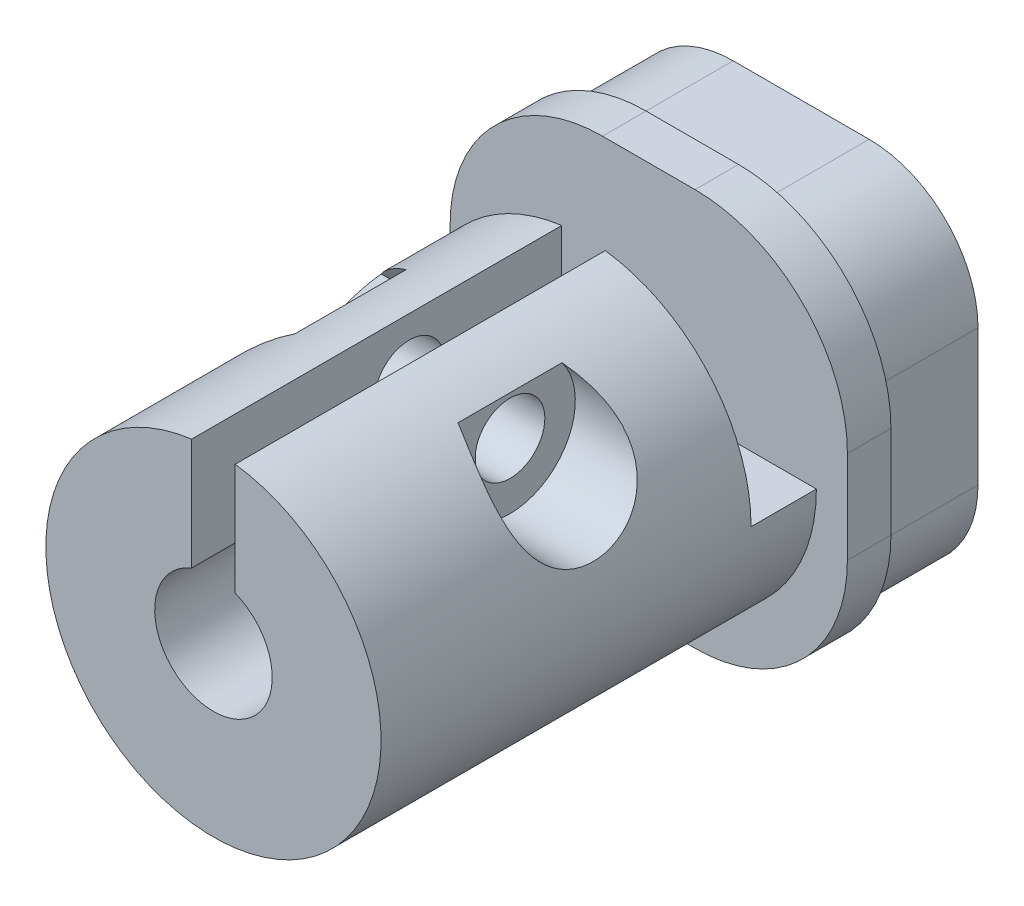
SolidWorks part; units mm, degrees
ref_plane "Płaszczyzna przednia" through (0, 0, 0) normal (0, 0, 1) x (1, 0, 0)
ref_plane "Płaszczyzna górna" through (0, 0, 0) normal (0, 1, 0) x (1, 0, 0)
ref_plane "Płaszczyzna prawa" through (0, 0, 0) normal (1, 0, 0) x (0, 0, -1)
sketch "Sketch1" plane through (0, 0, 0) normal (0, 0, 1) x (1, 0, 0)
  line L0 (6.125, 6.125) -> (-6.125, 6.125)
  line L1 (8.125, -8.125) -> (-8.125, -8.125)
  line L2 (8.125, -8.125) -> (8.125, 8.125)
  line L3 (8.125, 8.125) -> (-8.125, 8.125)
  line L4 (-8.125, -8.125) -> (-8.125, 8.125)
  line L5 (8.125, -8.125) -> (-8.125, 8.125) construction
  line L6 (8.125, 8.125) -> (-8.125, -8.125) construction
  line L7 (-6.125, -6.125) -> (-6.125, 6.125)
  line L8 (6.125, -6.125) -> (-6.125, -6.125)
  line L9 (6.125, -6.125) -> (6.125, 6.125)
  point P0 (0, 0)
  dimension "D1" = 16.25
  dimension "D2" = 2
extrude "Boss-Extrude1" add sketch "Sketch1" along normal blind 5
fillet "Fillet1" radius 5 8 edges at (-8.125, -8.125, 2.5) (8.125, -8.125, 2.5) (-8.125, 8.125, 2.5) (8.125, 8.125, 2.5) (6.125, -6.125, 2.5) (-6.125, -6.125, 2.5) (6.125, 6.125, 2.5) (-6.125, 6.125, 2.5)
sketch "Sketch2" plane through (0, 0, 5) normal (0, 0, 1) x (1, 0, 0)
  line L0 (-8.125, 3.125) -> (-8.125, -3.125) construction
  line L1 (9.125, 9.125) -> (-9.125, 9.125)
  line L2 (9.125, 9.125) -> (9.125, -9.125)
  line L3 (9.125, -9.125) -> (-9.125, -9.125)
  line L4 (-9.125, 9.125) -> (-9.125, -9.125)
  line L5 (9.125, 9.125) -> (-9.125, -9.125) construction
  line L6 (9.125, -9.125) -> (-9.125, 9.125) construction
  point P0 (0, 0)
  dimension "D1" = 1
extrude "Boss-Extrude2" add sketch "Sketch2" along normal blind 2
fillet "Fillet2" radius 7 4 edges at (9.125, -9.125, 6) (-9.125, -9.125, 6) (-9.125, 9.125, 6) (9.125, 9.125, 6)
sketch "Sketch3" plane through (0, 0, 7) normal (0, 0, 1) x (1, 0, 0)
  line L0 (0, 2.5) -> (0, 7.5) construction
  line L1 (1, 2.5) -> (1, 7.6348)
  line L2 (-1, 2.5) -> (-1, 7.6348)
  line L3 (1, 2.5) -> (1, 2.508)
  line L4 (-1, 2.5) -> (-1, 2.508)
  line L5 (-1, 2.5) -> (-1, 7.5) construction
  line L6 (1, 2.5) -> (1, 7.5) construction
  arc A0 (-1, 2.508) -> (1, 2.508) centre (0, 0) ccw
  arc A1 (-1, 7.6348) -> (1, 7.6348) centre (0, 0) ccw
  circle A2 centre (0, 0) radius 7.7 construction
  circle A3 centre (0, 0) radius 2.7 construction
  dimension "D1" = 5.4
  dimension "D2" = 5
  dimension "D3" = 1
  dimension "D4" = 1
extrude "Boss-Extrude3" add sketch "Sketch3" along normal blind 20 contours L2 A1 L1 A0
sketch "Sketch5" plane through (0, 0, 0) normal (1, 0, 0) x (0, 0, -1)
  line L0 (-27, -0.0326) -> (0, 0) construction
  line L2 (-27, 7.6348) -> (-27, -7.7) construction
  line L3 (-27, 7.6348) -> (-7, 7.6348) construction
  circle A0 centre (-17, 4.9795) radius 1.6
  point P2 (-27, -0.0326)
  point P5 (-17, 4.9795)
  point P12 (-17, 7.6348)
  dimension "D2" = 3.2
  dimension "D1" = 5
extrude "Cut-Extrude1" cut sketch "Sketch5" against normal through all both and the other way through all contours A0
ref_plane "Plane1" through (9.125, 0, 0) normal (1, 0, 0) x (0, 0, -1)
sketch "Sketch7" plane through (9.125, 0, 0) normal (1, 0, 0) x (0, 0, -1)
  circle A0 centre (-17, 4.9795) radius 3
  dimension "D1" = 6
extrude "Cut-Extrude2" cut sketch "Sketch7" against normal blind 5.5
ref_plane "Plane2" through (-7.7, 0, 0) normal (-1, 0, 0) x (0, 0, 1)
sketch "Sketch8" plane through (-7.7, 0, 0) normal (-1, 0, 0) x (0, 0, 1)
  line L1 (13.4204, 4.9795) -> (15.2102, 1.8795)
  line L2 (15.2102, 1.8795) -> (18.7898, 1.8795)
  line L3 (18.7898, 1.8795) -> (20.5796, 4.9795)
  line L4 (20.5796, 4.9795) -> (18.7898, 8.0795)
  line L5 (18.7898, 8.0795) -> (15.2102, 8.0795)
  line L6 (15.2102, 8.0795) -> (13.4204, 4.9795)
  circle A0 centre (17, 4.9795) radius 3.1 construction
  dimension "D1" = 6.2
extrude "Cut-Extrude3" cut sketch "Sketch8" against normal blind 4
sketch "Sketch9" plane through (-7.7, 0, 0) normal (-1, 0, 0) x (0, 0, 1)
  line L0 (5, 2.125) -> (5, -2.125) construction
  line L1 (7, 10.7439) -> (10, 10.7439)
  line L2 (7, 10.7439) -> (7, 0)
  line L3 (7, 0) -> (10, 0)
  line L4 (10, 10.7439) -> (10, 0)
  point P7 (5, 0)
  dimension "D1" = 3
  dimension "D2" = 7
extrude "Cut-Extrude4" cut sketch "Sketch9" against normal through all
